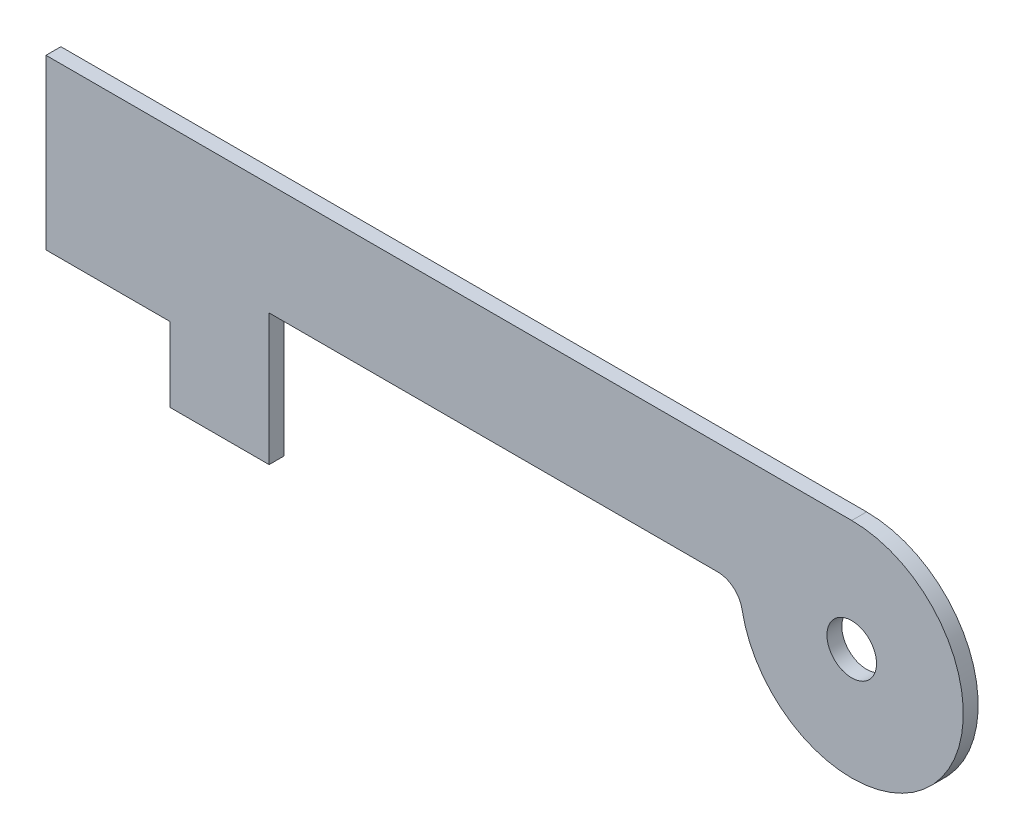
SolidWorks part; units mm, degrees
ref_plane "Front Plane" through (0, 0, 0) normal (0, 0, 1) x (1, 0, 0)
ref_plane "Top Plane" through (0, 0, 0) normal (0, 1, 0) x (1, 0, 0)
ref_plane "Right Plane" through (0, 0, 0) normal (1, 0, 0) x (0, 0, -1)
sketch "Sketch1" plane through (0, 0, 0) normal (0, 0, 1) x (1, 0, 0)
  line L0 (-5, 5) -> (-5, 9)
  line L8 (5, -5) -> (-5, -5)
  line L9 (5, -5) -> (5, 5)
  line L10 (5, 5) -> (-5, 5)
  line L11 (-5, -5) -> (-5, 5)
  line L12 (5, -5) -> (-5, 5) construction
  line L13 (5, 5) -> (-5, -5) construction
  line L14 (-5, 9) -> (-2.4058, 18.1799)
  line L15 (0, -55) -> (0, 55) construction
  line L16 (9, 5) -> (18.1799, 2.4058)
  line L17 (5, 5) -> (5, 9)
  line L18 (55, 0) -> (-55, 0) construction
  line L19 (5, -5) -> (5, -9)
  line L20 (-5, -9) -> (-2.4058, -18.1799)
  line L21 (5, -9) -> (2.4058, -18.1799)
  line L22 (-5, -5) -> (-5, -9)
  line L23 (5, -5) -> (9, -5)
  line L24 (9, -5) -> (18.1799, -2.4058)
  line L25 (-9, -5) -> (-18.1799, -2.4058)
  line L26 (5, 5) -> (9, 5)
  line L27 (-5, -5) -> (-9, -5)
  line L28 (-9, 5) -> (-18.1799, 2.4058)
  line L29 (5, 9) -> (2.4058, 18.1799)
  line L30 (-5, 5) -> (-9, 5)
  line L31 (0, 22.5) -> (-22.5, 0)
  line L32 (-22.5, 0) -> (-22.5, 22.5)
  line L33 (-22.5, 22.5) -> (0, 22.5)
  line L34 (-27.0416, 0) -> (-22.5, 0)
  line L35 (-22.5, 22.5) -> (-162.5, 22.5)
  line L36 (-22.5, 22.5) -> (-22.5, 0)
  line L37 (-22.5, 0) -> (-117.5, 0)
  line L38 (-162.5, 22.5) -> (-162.5, -11.5)
  line L41 (-22.5, 0) -> (-22.125, -4.0909)
  line L44 (-137.5, -11.5) -> (-137.5, -26.5)
  line L45 (-137.5, -26.5) -> (-117.5, -26.5)
  line L46 (-117.5, 0) -> (-117.5, -26.5)
  line L48 (-137.5, -11.5) -> (-162.5, -11.5)
  circle A0 centre (0, 0) radius 22.5
  circle A1 centre (0, 17.5) radius 2.5
  circle A2 centre (0, -17.5) radius 2.5
  circle A3 centre (17.5, 0) radius 2.5
  circle A4 centre (-17.5, 0) radius 2.5
  circle A5 centre (-7.5, 7.5) radius 2.5
  circle A6 centre (-7.5, -7.5) radius 2.5
  circle A7 centre (7.5, 7.5) radius 2.5
  circle A8 centre (7.5, -7.5) radius 2.5
  arc A9 (-27.0416, 0) -> (-22.125, -4.0909) centre (-27.0416, -5) cw
  dimension "D1" = 45
  dimension "D3" = 5
  dimension "D5" = 12.5
  dimension "D6" = 5
  dimension "D9" = 5
  dimension "D11" = 5
  dimension "D2" = 10
  dimension "D4" = 4
  dimension "D7" = 4
  dimension "D8" = 12.5
  dimension "D10" = 140
  dimension "D12" = 15
  dimension "D13" = 20
  dimension "D14" = 25
  dimension "D15" = 34
extrude "Boss-Extrude1" add sketch "Sketch1" along normal blind 3
sketch "Sketch3" plane through (0, 0, 3) normal (0, 0, 1) x (1, 0, 0)
  circle A0 centre (0, 0) radius 5
  circle A1 centre (0, 0) radius 22.5
  arc A2 (-22.125, -4.0909) -> (0, 22.5) centre (0, 0) ccw construction
  dimension "D1" = 10
extrude "Boss-Extrude2" add sketch "Sketch3" against normal up to surface (3 mm away) up to face at (-95.0076, -6.4219, 0)
sketch "Sketch4" [suppressed] plane through (0, 0, 3) normal (0, 0, 1) x (1, 0, 0)
  line L0 (-162.5, 22.5) -> (0, 22.5) construction
  line L3 (-162.5, 22.5) -> (0, 22.5)
  line L7 (-27.0416, 0) -> (-102.5, 0) construction
  line L8 (-102.5, 0) -> (-102.5, -26.5) construction
  line L9 (-132.5, -26.5) -> (-102.5, -26.5) construction
  line L10 (-132.5, -11.5) -> (-132.5, -26.5) construction
  line L11 (-132.5, -11.5) -> (-162.5, -11.5) construction
  line L12 (-162.5, 22.5) -> (-162.5, -11.5) construction
  line L13 (-27.0416, 0) -> (-102.5, 0)
  line L14 (-102.5, 0) -> (-102.5, -26.5)
  line L15 (-132.5, -26.5) -> (-102.5, -26.5)
  line L16 (-132.5, -11.5) -> (-132.5, -26.5)
  line L17 (-132.5, -11.5) -> (-162.5, -11.5)
  line L18 (-162.5, 22.5) -> (-162.5, -11.5)
  arc A0 (0, 22.5) -> (-22.125, -4.0909) centre (0, 0) ccw
  arc A1 (-22.125, -4.0909) -> (0, 22.5) centre (0, 0) ccw construction
  arc A2 (-22.125, -4.0909) -> (-27.0416, 0) centre (-27.0416, -5) ccw construction
  arc A3 (-22.125, -4.0909) -> (-27.0416, 0) centre (-27.0416, -5) ccw
extrude "Cut-Extrude1" [suppressed] cut sketch "Sketch4" against normal through all
sketch "Sketch5" [suppressed] plane through (0, 0, 0) normal (0, 0, -1) x (-1, 0, 0)
  circle A0 centre (0, 0) radius 5
  circle A2 centre (0, 0) radius 22.5
  circle A5 centre (0, 0) radius 22.5 construction
  dimension "D1" = 10
extrude "Boss-Extrude3" [suppressed] add sketch "Sketch5" against normal up to surface (3 mm away)
sketch "Sketch6" [suppressed] plane through (0, 0, 3) normal (0, 0, 1) x (1, 0, 0)
  line L0 (7.6955, 21.1431) -> (54.6801, 4.0421)
  line L1 (68.994, -41.356) -> (62.4408, -36.7674)
  line L2 (39.7279, 0.9708) -> (51.9439, -3.4755)
  line L3 (7.6955, 21.1431) -> (0, 0) construction
  line L4 (0, 0) -> (21.1431, -7.6955) construction
  line L5 (0, -1000) -> (0, 49000) construction
  arc A0 (54.6801, 4.0421) -> (68.994, -41.356) centre (44.4195, -24.1487) cw
  arc A2 (21.1431, -7.6955) -> (7.6955, 21.1431) centre (0, 0) ccw
  arc A3 (51.9439, -3.4755) -> (62.4408, -36.7674) centre (44.4195, -24.1487) cw
  circle A4 centre (0, 0) radius 22.5 construction
  arc A5 (21.1431, -7.6955) -> (39.7279, 0.9708) centre (34.7686, -12.6547) cw
  dimension "D2" = 22
  dimension "D1" = 8
  dimension "D3" = 50
  dimension "D4" = 20
  dimension "D5" = 15
extrude "Boss-Extrude4" [suppressed] add sketch "Sketch6" against normal up to surface (3 mm away)
sketch "Sketch7" [suppressed] plane through (0, 0, 3) normal (0, 0, 1) x (1, 0, 0)
  line L0 (54.6801, 4.0421) -> (51.9439, -3.4755)
  line L1 (54.6801, 4.0421) -> (7.6955, 21.1431) construction
  line L2 (39.7279, 0.9708) -> (51.9439, -3.4755) construction
  line L3 (39.7279, 0.9708) -> (51.9439, -3.4755)
  line L4 (54.6801, 4.0421) -> (7.6955, 21.1431)
  arc A0 (39.7279, 0.9708) -> (21.1431, -7.6955) centre (34.7686, -12.6547) ccw construction
  arc A1 (7.6955, 21.1431) -> (21.1431, -7.6955) centre (0, 0) ccw construction
  arc A2 (39.7279, 0.9708) -> (21.1431, -7.6955) centre (34.7686, -12.6547) ccw
  arc A3 (7.6955, 21.1431) -> (21.1431, -7.6955) centre (0, 0) ccw
extrude "Cut-Extrude2" [suppressed] cut sketch "Sketch7" against normal through all
ref_plane "Plane1" [suppressed] through (0, 0, 1.5) normal (0, 0, -1) x (-1, 0, 0)
